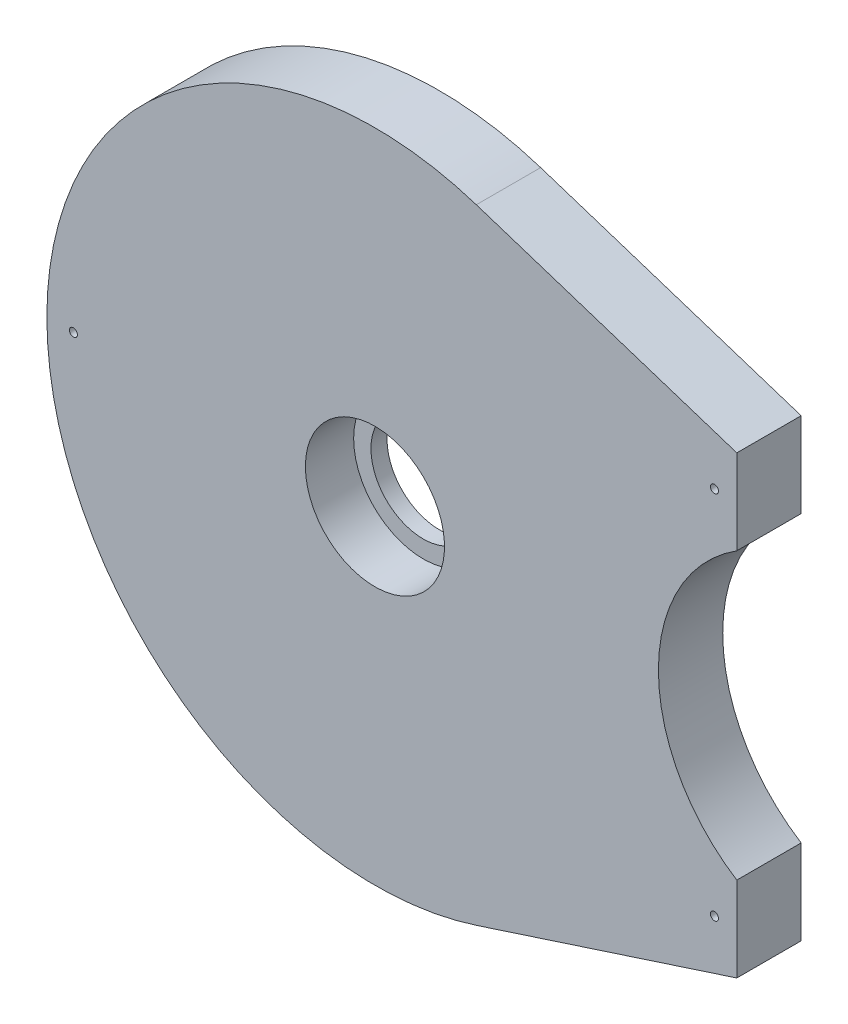
SolidWorks part; units mm, degrees
ref_plane "前视基准面" through (0, 0, 0) normal (0, 0, 1) x (1, 0, 0)
ref_plane "上视基准面" through (0, 0, 0) normal (0, 1, 0) x (1, 0, 0)
ref_plane "右视基准面" through (0, 0, 0) normal (1, 0, 0) x (0, 0, -1)
other "Configuration Table"
sketch "草图1" plane through (0, 0, 0) normal (0, 0, 1) x (1, 0, 0)
  circle A0 centre (0, 0) radius 40.8
  dimension "D1" = 81.6
extrude "凸台-拉伸1" add sketch "草图1" along normal mid plane 8
sketch "草图2" plane through (0, 0, 0) normal (0, 1, 0) x (1, 0, 0)
  line L0 (0, 4) -> (0, -4)
  line L1 (0, -4) -> (8.65, -4)
  line L2 (8.65, -4) -> (8.65, 2)
  line L3 (8.65, 2) -> (6.5, 2)
  line L4 (6.5, 2) -> (6.5, 4)
  line L5 (6.5, 4) -> (0, 4)
  line L6 (40.8, 4) -> (-40.8, 4) construction
  line L7 (-40.8, -4) -> (40.8, -4) construction
  dimension "D1" = 6.5
  dimension "D2" = 8.65
  dimension "D3" = 6
revolve "切除-旋转2" cut sketch "草图2" angle 360 about L0
sketch "草图3" plane through (0, 0, 0) normal (0, 1, 0) x (1, 0, 0)
  line L0 (0, 0) -> (0, 23.471) construction
  line L1 (40.8, 4) -> (-40.8, 4) construction
  circle A0 centre (31, 5) radius 3.15
  dimension "D1" = 6.3
  dimension "D2" = 31
  dimension "D3" = 1
revolve "切除-旋转3" cut sketch "草图3" angle 360 about L0
sketch "草图4" plane through (0, 0, -4) normal (0, 0, -1) x (-1, 0, 0)
  line L0 (0, 0) -> (-68.7118, 0) construction
  line L1 (-36, 19.2) -> (-36, -19.2)
  line L2 (-40.8, 0) -> (-40.8, 19.2)
  line L3 (-40.8, 19.2) -> (-36, 19.2)
  line L4 (-36, -19.2) -> (-40.8, -19.2)
  line L5 (-40.8, -19.2) -> (-40.8, 0)
  circle A0 centre (0, 0) radius 40.8 construction
  dimension "D1" = 36
extrude "切除-拉伸1" cut sketch "草图4" against normal blind 10
sketch "草图5" plane through (0, 0, -4) normal (0, 0, -1) x (-1, 0, 0)
  line L0 (0, 0) -> (-36.1567, 0) construction
  line L2 (-45, 28.2783) -> (-45, -28.2783)
  line L3 (-45, 28.2783) -> (-12.6079, 38.8031)
  line L4 (-45, -28.2783) -> (-12.6079, -38.8031)
  line L6 (-36, -19.2) -> (-36, 19.2) construction
  line L7 (-34.8764, 21.1726) -> (-34.1774, -22.2833)
  line L8 (-40.8, 0) -> (-65.1741, 0) construction
  arc A0 (-36, -19.2) -> (-36, 19.2) centre (0, 0) ccw construction
  arc A2 (-12.6079, 38.8031) -> (-36, 19.2) centre (0, 0) ccw
  arc A3 (-34.1774, -22.2833) -> (-12.6079, -38.8031) centre (0, 0) ccw
  point P16 (-34.8764, 21.1726)
  dimension "D2" = 18
  dimension "D3" = 18
extrude "凸台-拉伸3" add sketch "草图5" against normal up to surface (8 mm away) up to face at (-2.4, 0, 4)
sketch "草图6" plane through (0, 0, -4) normal (0, 0, -1) x (-1, 0, 0)
  line L0 (0, 0) -> (-69.1717, 0) construction
  circle A0 centre (-56.25, 0) radius 21
  point P5 (0, 0)
  point P6 (0, 0)
  dimension "D2" = 42
  dimension "D1" = 56.25
extrude "切除-拉伸2" cut sketch "草图6" against normal blind 10
sketch "草图7" plane through (0, 0, -4) normal (0, 0, -1) x (-1, 0, 0)
  circle A0 centre (-42.2196, 23.0053) radius 0.5
  circle A1 centre (-42.2196, -23.0053) radius 0.5
  circle A2 centre (37.5, 0) radius 0.5
  dimension "D2" = 1
  dimension "D3" = 1
  dimension "D4" = 1
  dimension "D1" = 37.5
extrude "切除-拉伸3" cut sketch "草图7" against normal blind 10
